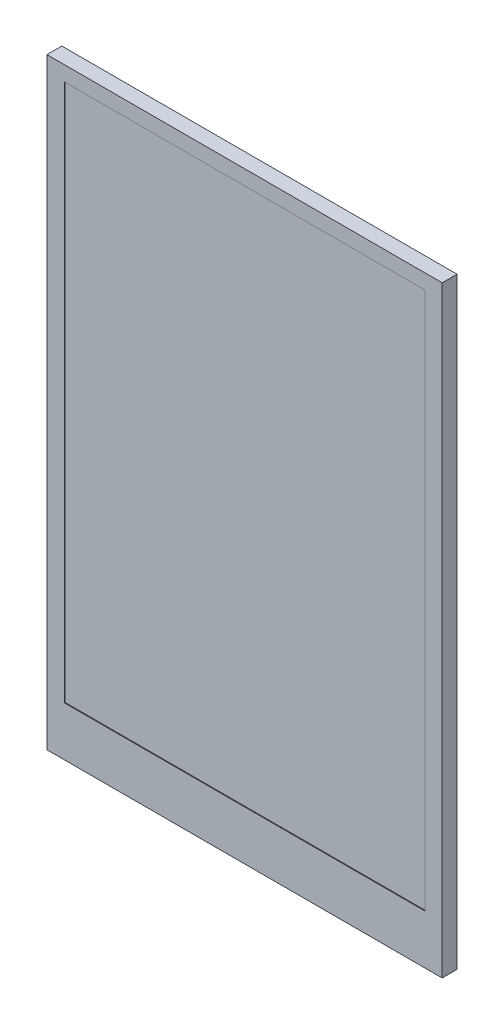
SolidWorks part; units mm, degrees
ref_plane "前视基准面" through (0, 0, 0) normal (0, 0, 1) x (1, 0, 0)
ref_plane "上视基准面" through (0, 0, 0) normal (0, 1, 0) x (1, 0, 0)
ref_plane "右视基准面" through (0, 0, 0) normal (1, 0, 0) x (0, 0, -1)
sketch "草图1" plane through (0, 0, 0) normal (0, 0, 1) x (1, 0, 0)
  line L1 (-27.23, -41.47) -> (27.23, -41.47)
  line L2 (-27.23, -41.47) -> (-27.23, 41.47)
  line L3 (-27.23, 41.47) -> (27.23, 41.47)
  line L4 (27.23, -41.47) -> (27.23, 41.47)
  line L5 (-27.23, -41.47) -> (27.23, 41.47) construction
  line L6 (-27.23, 41.47) -> (27.23, -41.47) construction
  point P0 (0, 0)
  dimension "D1" = 82.94
  dimension "D2" = 54.46
extrude "凸台-拉伸1" add sketch "草图1" along normal blind 2.05
sketch "草图2" plane through (0, 0, 2.05) normal (0, 0, 1) x (1, 0, 0)
  line L0 (27.23, -41.47) -> (27.23, 41.47) construction
  line L1 (-24.83, 39.42) -> (24.83, 39.42)
  line L2 (-24.83, 39.42) -> (-24.83, -34.67)
  line L3 (-24.83, -34.67) -> (24.83, -34.67)
  line L4 (24.83, 39.42) -> (24.83, -34.67)
  line L5 (27.23, 41.47) -> (-27.23, 41.47) construction
  point P0 (0, 0)
  dimension "D1" = 49.66
  dimension "D2" = 74.09
  dimension "D3" = 2.4
  dimension "D4" = 2.05
extrude "切除-拉伸1" cut sketch "草图2" against normal blind 0.1
ref_plane "排线起点" through (18, 0, 0) normal (1, 0, 0) x (0, 0, -1)
sketch "草图3" [suppressed] plane through (0, -41.47, 0) normal (0, -1, 0) x (1, 0, 0)
  line L1 (-14.138, 0.2) -> (17.9531, 0.2)
  line L2 (-14.138, 0.2) -> (-14.138, 0.7)
  line L3 (-14.138, 0.7) -> (17.9531, 0.7)
  line L4 (17.9531, 0.2) -> (17.9531, 0.7)
  line L5 (-27.23, 0) -> (27.23, 0) construction
  dimension "D1" = 0.2
  dimension "D2" = 0.5
extrude "排线" [suppressed] add sketch "草图3" along normal blind 44.9
sketch "草图4" [suppressed] plane through (0, 0, 0.7) normal (0, 0, 1) x (1, 0, 0)
  line L0 (1.9075, -88.9253) -> (1.9075, -26.6835) construction
  line L1 (17.9531, -86.37) -> (7.1581, -86.37)
  line L2 (17.9531, -86.37) -> (17.9531, -61.0529)
  line L3 (17.9531, -61.0529) -> (7.1581, -61.0529)
  line L4 (7.1581, -86.37) -> (7.1581, -61.0529)
  line L5 (-14.138, -86.37) -> (-6.306, -86.37)
  line L6 (-14.138, -86.37) -> (-14.138, -61.0529)
  line L7 (-14.138, -61.0529) -> (-6.306, -61.0529)
  line L8 (-6.306, -86.37) -> (-6.306, -61.0529)
  line L9 (-14.138, -41.47) -> (-7.3116, -41.47)
  line L10 (-14.138, -41.47) -> (-14.138, -45.7804)
  line L11 (-14.138, -45.7804) -> (-7.3116, -45.7804)
  line L12 (-7.3116, -41.47) -> (-7.3116, -45.7804)
  line L13 (11.1266, -41.47) -> (11.1266, -45.7804)
  line L14 (17.9531, -45.7804) -> (11.1266, -45.7804)
  line L15 (17.9531, -41.47) -> (17.9531, -45.7804)
  line L16 (17.9531, -41.47) -> (11.1266, -41.47)
extrude "切除-拉伸2" [suppressed] cut sketch "草图4" against normal blind 44.9
fillet "圆角1" [suppressed] radius 2
sketch "草图7" plane through (18, 0, 0) normal (1, 0, 0) x (0, 0, -1)
  line L0 (-2.05, -41.47) -> (0, -41.47) construction
  line L1 (5.1466, -3.47) -> (5.444, -3.4311)
  line L2 (-1.2863, -41.6174) -> (-1.025, -41.47)
  spline S0 degree 3 poles (-1.025, -41.47) (0.5861, -44.3263) (2.7244, -41.577) (1.1671, -39.243) (-0.4743, -35.1377) (2.4131, -28.2532) (-0.61, -19.9407) (2.6041, -13.342) (4.7613, -8.3259) (5.3444, -4.983) (5.1466, -3.47) knots 0 0 0 0 0.09978 0.14739 0.187617 0.406025 0.616639 0.76383 0.898121 1 1 1 1
  spline S1 degree 1 poles (-1.2863, -41.6174) (5.444, -3.4311) knots 0 0 1 1 construction
  spline S2 degree 3 poles (-1.2863, -41.6174) (-1.2236, -41.7286) (-1.088, -41.9548) (-0.8272, -42.3351) (-0.4966, -42.7219) (-0.0967, -43.0437) (0.4495, -43.2989) (1.1403, -43.2574) (1.7397, -42.7721) (2.1128, -42.09) (2.2832, -41.3056) (2.1969, -40.5254) (1.9194, -39.8542) (1.5788, -39.2403) (1.1732, -38.4605) (0.8029, -37.4501) (0.6059, -36.2175) (0.6004, -34.5176) (0.9432, -32.3075) (1.3706, -30.0233) (1.5203, -28.1629) (1.4572, -26.3055) (1.1186, -24.0325) (0.7166, -21.3784) (0.7391, -18.8459) (1.5031, -16.3578) (2.638, -13.8682) (3.7776, -11.3854) (4.7418, -8.874) (5.3437, -6.6922) (5.5459, -4.8655) (5.5055, -3.9015) (5.444, -3.4311) knots 0 0 0 0 0.003906 0.007812 0.015625 0.023438 0.03125 0.046875 0.0625 0.078125 0.09375 0.109375 0.125 0.140625 0.15625 0.1875 0.21875 0.25 0.3125 0.375 0.40625 0.4375 0.5 0.5625 0.625 0.6875 0.75 0.8125 0.875 0.9375 0.96875 1 1 1 1
  point P2 (0.5174, -19.1518)
  point P4 (0, 0)
  point P6 (0.5527, -37.5184)
  point P8 (1.4931, -28.1776)
  point P10 (1.9406, -41.0236)
  point P12 (1.1817, -39.1263)
  dimension "D1" = 38
  dimension "D2" = 0.3
extrude "凸台-拉伸3" add sketch "草图7" against normal blind 30 separate body
sketch "草图8" plane through (0, 0, 0) normal (0, 0, -1) x (-1, 0, 0)
  line L0 (-3, -3.4311) -> (-3, -57.7316) construction
  line L1 (12, -3.4311) -> (-18, -3.4311) construction
  line L2 (-18, 11.8658) -> (-18, -11.8658) construction
  line L3 (-18, -3.4128) -> (-11.3851, -3.4128)
  line L4 (-18, -3.4128) -> (-18, -16.1241)
  line L5 (-18, -16.1241) -> (-11.3851, -16.1241)
  line L6 (-11.3851, -3.4128) -> (-11.3851, -16.1241)
  line L7 (12, -43.2622) -> (12, -3.4311) construction
  line L8 (12, -3.4311) -> (4.3118, -3.4311)
  line L9 (12, -3.4311) -> (12, -16.1241)
  line L10 (12, -16.1241) -> (4.3118, -16.1241)
  line L11 (4.3118, -3.4311) -> (4.3118, -16.1241)
  line L12 (12, -42.8664) -> (5.0211, -42.8664)
  line L13 (12, -42.8664) -> (12, -33.9262)
  line L14 (12, -33.9262) -> (5.0211, -33.9262)
  line L15 (5.0211, -42.8664) -> (5.0211, -33.9262)
  line L17 (-18, -42.8664) -> (-10.2249, -42.8664)
  line L18 (-18, -42.8664) -> (-18, -33.9262)
  line L19 (-18, -33.9262) -> (-10.2249, -33.9262)
  line L20 (-10.2249, -42.8664) -> (-10.2249, -33.9262)
extrude "切除-拉伸4" cut sketch "草图8" along normal blind 30
